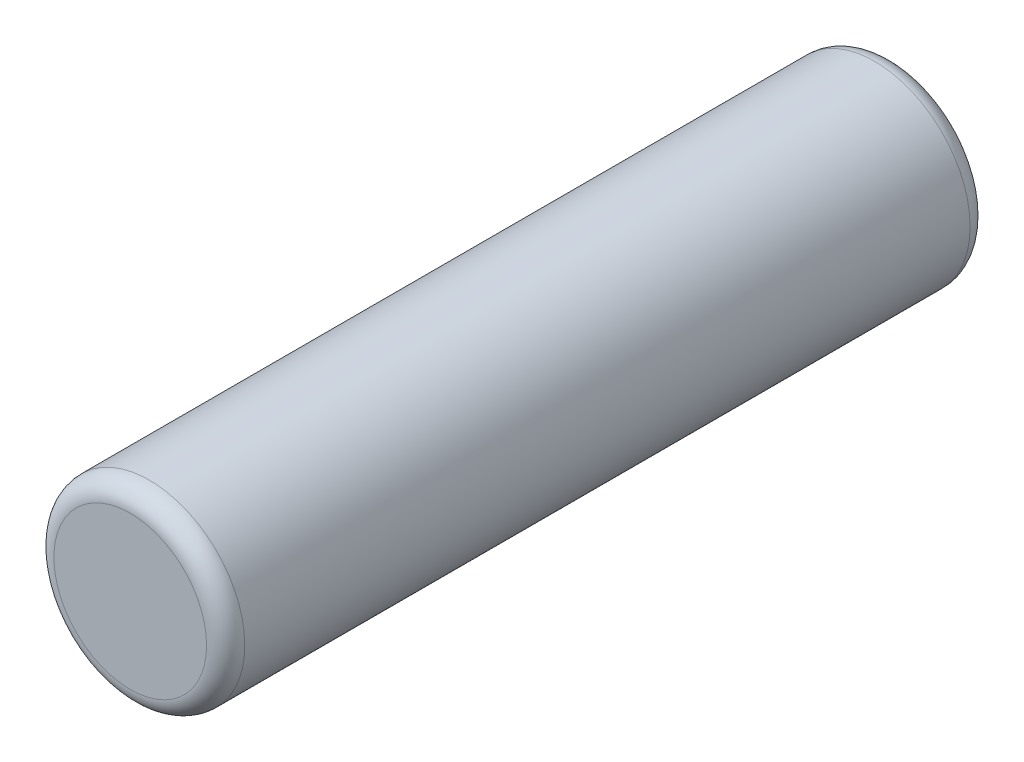
SolidWorks part; units mm, degrees
ref_plane "Front Plane" through (0, 0, 0) normal (0, 0, 1) x (1, 0, 0)
ref_plane "Top Plane" through (0, 0, 0) normal (0, 1, 0) x (1, 0, 0)
ref_plane "Right Plane" through (0, 0, 0) normal (1, 0, 0) x (0, 0, -1)
sketch "Sketch2" plane through (0, 0, 0) normal (0, 0, 1) x (1, 0, 0)
  circle A0 centre (0, 0) radius 2.5
  dimension "D1" = 5
extrude "Boss-Extrude1" add sketch "Sketch2" along normal blind 20
fillet "Fillet1" radius 0.5 2 edges at (2.5, 0, 0) (2.5, 0, 20)
